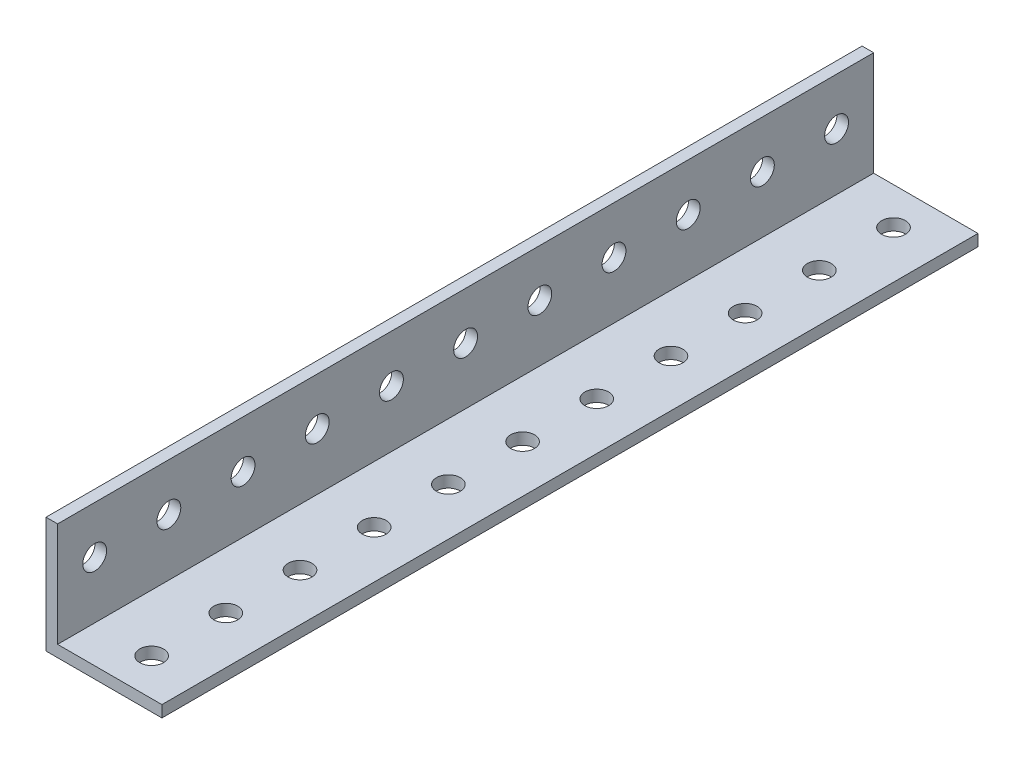
SolidWorks part; units mm, degrees
material "6061-T6 (SS)"
ref_plane "Front Plane" through (0, 0, 0) normal (0, 0, 1) x (1, 0, 0)
ref_plane "Top Plane" through (0, 0, 0) normal (0, 1, 0) x (1, 0, 0)
ref_plane "Right Plane" through (0, 0, 0) normal (1, 0, 0) x (0, 0, -1)
sketch "Sketch1" plane through (0, 0, 0) normal (0, 0, 1) x (1, 0, 0)
  line L0 (0, 0) -> (0, 15.875)
  line L1 (0, 15.875) -> (1.5875, 15.875)
  line L2 (1.5875, 15.875) -> (1.5875, 1.5875)
  line L3 (1.5875, 1.5875) -> (15.875, 1.5875)
  line L4 (15.875, 1.5875) -> (15.875, 0)
  line L5 (15.875, 0) -> (0, 0)
  dimension "D1" = 15.875
  dimension "D2" = 1.5875
  dimension "D3" = 15.875
extrude "Extrude1" add sketch "Sketch1" along normal blind 111.76
sketch "Sketch2" plane through (0, 1.5875, 0) normal (0, 1, 0) x (1, 0, 0)
  line L0 (15.875, -55.88) -> (9.3853, -55.88) construction
  line L1 (9.3853, -55.88) -> (1.5875, -55.88) construction
  line L2 (1.5875, -111.76) -> (1.5875, 0) construction
  line L3 (15.875, -111.76) -> (15.875, 0) construction
  point P6 (7.1437, -55.88)
  dimension "D1" = 7.7978
hole_wizard "#4 Clearance Hole1" positions "3DSketch1" profile "Sketch3" hole size "#4" standard "Ansi Inch"
sketch3d "3DSketch1"
  point P4 (9.3853, 1.5875, 55.88)
sketch "Sketch3" plane through (9.3853, 1.5875, 55.88) normal (1, 0, 0) x (0, 0, 1)
  line L0 (0, 0) -> (0, 16.2206)
  line L1 (0, 16.2206) -> (1.6319, 15.24)
  line L2 (1.6319, 15.24) -> (1.6319, 0)
  line L5 (1.6319, 0) -> (0, 0)
  line L10 (0, 16.2206) -> (-1.6319, 15.24) construction
  line L11 (0, -6.35) -> (0, 107.95) construction
  dimension "Hole Dia." = 3.2639
  dimension "Hole Depth" = 15.24
  dimension "Drill Angle" = 118
pattern_linear "LPattern1" count 6 spacing 10.16 along (0, 0, 1) count 6 spacing 10.16 along (0, 0, -1) of "#4 Clearance Hole1"
sketch "Sketch4" plane through (1.5875, 0, 0) normal (1, 0, 0) x (0, 0, -1)
  line L1 (-55.88, 9.3726) -> (-55.88, 1.5875) construction
  line L2 (-111.76, 1.5875) -> (0, 1.5875) construction
  point P6 (-63.5, 7.1437)
  dimension "D1" = 7.7851
hole_wizard "#4 Clearance Hole2" positions "3DSketch2" profile "Sketch5" hole size "#4" standard "Ansi Inch"
sketch3d "3DSketch2"
  point P4 (1.5875, 9.3726, 55.88)
sketch "Sketch5" plane through (1.5875, 9.3726, 55.88) normal (0, 1, 0) x (0, 0, -1)
  line L0 (0, 0) -> (0, 16.2206)
  line L1 (0, 16.2206) -> (1.6319, 15.24)
  line L2 (1.6319, 15.24) -> (1.6319, 0)
  line L5 (1.6319, 0) -> (0, 0)
  line L10 (0, 16.2206) -> (-1.6319, 15.24) construction
  line L11 (0, -6.35) -> (0, 107.95) construction
  dimension "Hole Dia." = 3.2639
  dimension "Hole Depth" = 15.24
  dimension "Drill Angle" = 118
pattern_linear "LPattern2" count 6 spacing 10.16 along (0, 0, 1) count 6 spacing 10.16 along (0, 0, -1) of "#4 Clearance Hole2"
chamfer "Chamfer1" [suppressed] distance 10.16 angle 45
